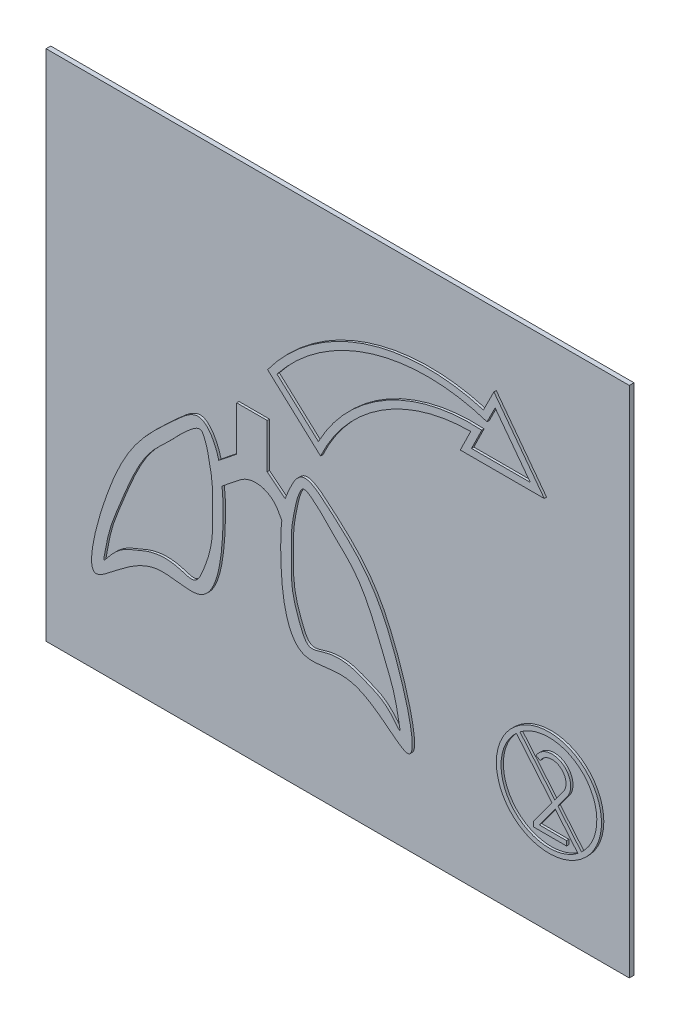
SolidWorks part; units mm, degrees
ref_plane "Face" through (0, 0, 0) normal (0, 0, 1) x (1, 0, 0)
ref_plane "Dessus" through (0, 0, 0) normal (0, 1, 0) x (1, 0, 0)
ref_plane "Droite" through (0, 0, 0) normal (1, 0, 0) x (0, 0, -1)
sketch "Esquisse1" plane through (0, 0, 0) normal (0, 0, 1) x (1, 0, 0)
  line L0 (0, 25.0031) -> (0, -26.9875) construction
  line L2 (12.5, -10) -> (12.5, 12)
  line L4 (-12.5, -10) -> (-12.5, 12)
  line L5 (-25.7969, 0) -> (27.3844, 0) construction
  line L6 (-12.5, 12) -> (12.5, 12)
  line L7 (-12.5, -10) -> (12.5, -10)
extrude "Extrusion1" add sketch "Esquisse1" along normal blind 0.2
sketch "Esquisse2" plane through (-107.9481, -44.9666, 0.2) normal (0, 0, 1) x (1, 0, 0)
  line L10 (105.7707, 48.6272) -> (105.7707, 36.6449) construction
  line L12 (102.9493, 45.4834) -> (103.7203, 46.0981)
  line L13 (103.0901, 44.6014) -> (103.8565, 45.2124)
  line L14 (105.6544, 44.6014) -> (105.4914, 44.8922)
  line L15 (105.7953, 45.4834) -> (105.0243, 46.0981)
  line L16 (103.7203, 46.0981) -> (103.7203, 48.0051)
  line L17 (105.0243, 46.0981) -> (105.0243, 48.0051)
  line L18 (103.7203, 48.0051) -> (105.0243, 48.0051)
  line L19 (103.0901, 44.6014) -> (103.1871, 43.6776) construction
  line L20 (102.9493, 45.4834) -> (103.5878, 42.6824) construction
  line L21 (105.6544, 44.6014) -> (105.7953, 45.4834) construction
  line L22 (105.7953, 45.4834) -> (105.1577, 42.6863) construction
  arc A1 (105.4914, 44.8922) -> (103.8565, 45.2124) centre (104.5379, 44.3577) ccw
  spline S4 degree 3 poles (102.9493, 45.4834) (102.8426, 45.9515) (102.2695, 47.128) (99.9993, 45.0784) (98.4973, 43.6138) (96.7378, 37.0059) (99.796, 40.7395) (102.8266, 39.3809) (103.137, 42.4546) (103.1491, 43.9184) (103.1086, 44.4252) (103.0901, 44.6014) knots 0 0 0 0 0.070215 0.126353 0.353004 0.536809 0.674978 0.772478 0.926638 0.974096 1 1 1 1
  spline S5 degree 3 poles (105.7953, 45.4834) (106.0231, 46.0577) (106.4329, 47.091) (108.7931, 45.1204) (110.232, 43.6005) (112.0098, 37.0082) (108.9475, 40.7392) (105.9203, 39.3807) (105.5981, 42.4558) (105.6035, 43.9173) (105.6265, 44.4265) (105.6544, 44.6014) knots 0 0 0 0 0.070215 0.126353 0.353004 0.536809 0.674978 0.772478 0.926638 0.974096 1 1 1 1
  spline S6 degree 3 poles (102.4611, 41.4465) (102.7238, 42.3995) (102.6648, 43.5309) (102.7117, 44.4125) (102.5447, 45.2729) (102.4132, 45.8803) (102.1564, 46.3476) (101.4027, 45.7828) (100.9354, 45.205) (99.9759, 44.3645) (99.2692, 43.1594) (98.7915, 41.9231) (98.2563, 40.6339) (98.14, 40.0172) (98.0002, 39.2477) (98.6129, 40.0765) (99.099, 40.2458) (100.2213, 40.7371) (101.05, 40.7387) (101.9757, 40.3615) (102.4611, 41.4465) (102.7238, 42.3995) (102.6648, 43.5309) knots -0.156403 -0.126464 -0.089597 0 0.047674 0.089922 0.14325 0.187046 0.193767 0.222788 0.290666 0.343022 0.419866 0.515238 0.560384 0.637512 0.643695 0.656746 0.736019 0.772226 0.843597 0.873536 0.910403 1 1.047674 1.089922 1.14325 only from (102.6796, 42.6775) to (102.6796, 42.6775)
  spline S7 degree 3 poles (106.2835, 41.4465) (106.0208, 42.3995) (106.0798, 43.5309) (106.0329, 44.4125) (106.1999, 45.2729) (106.3314, 45.8803) (106.5882, 46.3476) (107.3418, 45.7828) (107.8092, 45.205) (108.7687, 44.3645) (109.4754, 43.1594) (109.953, 41.9231) (110.4882, 40.6339) (110.6046, 40.0172) (110.7443, 39.2477) (110.1316, 40.0765) (109.6456, 40.2458) (108.5233, 40.7371) (107.6946, 40.7387) (106.7688, 40.3615) (106.2835, 41.4465) (106.0208, 42.3995) (106.0798, 43.5309) knots -0.156403 -0.126464 -0.089597 0 0.047674 0.089922 0.14325 0.187046 0.193767 0.222788 0.290666 0.343022 0.419866 0.515238 0.560384 0.637512 0.643695 0.656746 0.736019 0.772226 0.843597 0.873536 0.910403 1 1.047674 1.089922 1.14325 only from (106.065, 42.6775) to (106.065, 42.6775)
extrude "Extrusion2" add sketch "Esquisse2" along normal blind 0.1
sketch "Esquisse5" plane through (-95.5844, -42.5713, 0.2) normal (0, 0, 1) x (1, 0, 0)
  line L0 (101.3874, 49.562) -> (100.9404, 48.6504)
  line L1 (102.3824, 51.5319) -> (101.9331, 50.634)
  line L2 (102.3824, 51.5319) -> (104.5404, 48.6504)
  line L3 (104.5404, 48.6504) -> (100.9404, 48.6504)
  line L4 (92.6805, 47.504) -> (94.9514, 45.431)
  line L5 (93.0849, 47.541) -> (94.8587, 45.9219)
  line L6 (102.4334, 50.9634) -> (102.0874, 50.272)
  line L7 (102.4334, 50.9634) -> (103.9409, 48.9504)
  line L8 (103.9409, 48.9504) -> (101.4216, 48.9504)
  line L9 (101.8611, 49.8468) -> (101.4216, 48.9504)
  arc A0 (101.9331, 50.634) -> (92.6805, 47.504) centre (99.5347, 42.4831) ccw
  arc A1 (101.3874, 49.562) -> (94.9514, 45.431) centre (101.3874, 42.4831) ccw
  arc A2 (101.8611, 49.8468) -> (94.8587, 45.9219) centre (101.3874, 42.4831) ccw
  arc A3 (102.0874, 50.272) -> (93.0849, 47.541) centre (99.5347, 42.4831) ccw
  dimension "D1" = 0.3
extrude "Extrusion3" add sketch "Esquisse5" along normal blind 0.1
sketch "Esquisse7" plane through (0, 0, 0.2) normal (0, 0, -1) x (-1, 0, 0)
  line L0 (-9.1561, -4.7392) -> (-7.3328, -2.5663) construction
  line L1 (-9.1561, -4.7392) -> (-9.1561, -2.2079) construction
  line L2 (-7.9144, -3.1038) -> (-9.4107, -4.887)
  line L3 (-7.7612, -3.2324) -> (-9.2893, -5.0535)
  line L4 (-9.7536, -4.417) -> (-9.4107, -4.887)
  line L5 (-8.4937, -6.1441) -> (-8.4937, -6.3441)
  line L6 (-8.4937, -6.3441) -> (-9.9118, -6.3441)
  line L7 (-9.9118, -6.3441) -> (-9.9118, -6.1441)
  line L8 (-9.9575, -4.4769) -> (-9.5431, -5.0449)
  line L9 (-8.7412, -6.1441) -> (-9.9118, -6.1441)
  line L12 (-8.7412, -6.1441) -> (-9.7118, -6.1441) construction
  line L20 (-8.605, -3.6354) -> (-8.7775, -3.7367)
  line L21 (-9.9152, -4.5349) -> (-8.7412, -6.1441) construction
  line L22 (-9.4217, -5.2113) -> (-8.7412, -6.1441)
  line L23 (-9.5431, -5.0449) -> (-10.5509, -6.2459)
  line L24 (-9.2893, -5.0535) -> (-8.4937, -6.1441)
  line L25 (-9.7536, -4.417) -> (-8.4937, -6.1441) construction
  line L26 (-9.4217, -5.2113) -> (-10.3977, -6.3745)
  line L27 (-8.7412, -6.1441) -> (-9.9118, -6.1441) construction
  line L28 (-9.7118, -6.1441) -> (-9.7118, -6.1441) construction
  line L29 (-8.7412, -6.1441) -> (-8.7412, -6.1441) construction
  line L30 (-10.0193, -4.3641) -> (-10.0193, -4.3641) construction
  line L31 (-10.0193, -4.3641) -> (-10.0193, -4.3641) construction
  line L32 (-10.0193, -4.3641) -> (-10.0193, -4.3641) construction
  line L33 (-10.0193, -4.3641) -> (-10.0193, -4.3641) construction
  line L34 (-10.0193, -4.3641) -> (-10.0193, -4.3641) construction
  line L35 (-10.0193, -4.3641) -> (-10.0193, -4.3641) construction
  line L36 (-10.0193, -4.3641) -> (-10.0193, -4.3641) construction
  circle A0 centre (-9.1561, -4.7392) radius 2.2533
  arc A1 (-10.3977, -6.3745) -> (-7.7612, -3.2324) centre (-9.1561, -4.7392) ccw
  circle A2 centre (-9.1561, -4.7392) radius 2.0533 construction
  arc A3 (-7.9144, -3.1038) -> (-10.5509, -6.2459) centre (-9.1561, -4.7392) ccw
  arc A4 (-9.7536, -4.417) -> (-8.7775, -3.7367) centre (-9.2919, -4.039) cw
  arc A5 (-9.9575, -4.4769) -> (-8.605, -3.6354) centre (-9.2919, -4.039) cw
  arc A6 (-10.0193, -4.3641) -> (-8.605, -3.6354) centre (-9.2919, -4.039) cw construction
  dimension "D2" = 40
  dimension "D3" = 0.1
  dimension "D4" = 0.2
  dimension "D1" = 0.2
  dimension "D5" = 0.2
extrude "Extrusion4" add sketch "Esquisse7" against normal blind 0.1
